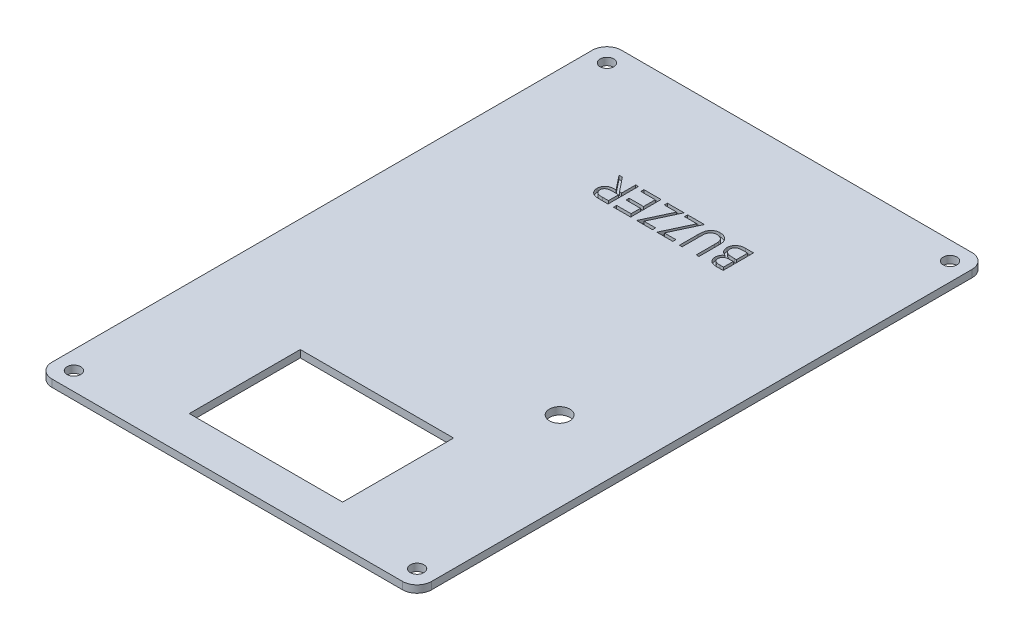
SolidWorks part; units mm, degrees
ref_plane "Front Plane" through (0, 0, 0) normal (0, 0, 1) x (1, 0, 0)
ref_plane "Top Plane" through (0, 0, 0) normal (0, 1, 0) x (1, 0, 0)
ref_plane "Right Plane" through (0, 0, 0) normal (1, 0, 0) x (0, 0, -1)
sketch "Sketch1" plane through (0, 0, 0) normal (0, 1, 0) x (1, 0, 0)
  line L1 (-34.4208, 88.2047) -> (31.6192, 88.2047)
  line L2 (-34.4208, 88.2047) -> (-34.4208, -10.8553)
  line L3 (-34.4208, -10.8553) -> (31.6192, -10.8553)
  line L4 (31.6192, 88.2047) -> (31.6192, -10.8553)
  line L6 (31.6192, -8.3153) -> (31.6192, -10.8553) construction
  line L7 (31.6192, -10.8553) -> (29.0792, -10.8553) construction
  line L8 (29.0792, -10.8553) -> (-31.8808, -10.8553) construction
  line L9 (-31.8808, -10.8553) -> (-34.4208, -10.8553) construction
  line L10 (-34.4208, -10.8553) -> (-34.4208, -8.3153) construction
  line L11 (-31.8808, 88.2047) -> (-34.4208, 88.2047) construction
  line L12 (-34.4208, 88.2047) -> (-34.4208, 85.6647) construction
  arc A3 (-31.8808, 88.2047) -> (-34.4208, 85.6647) centre (-31.8808, 85.6647) ccw construction
  point P4 (0, 0)
  point P12 (31.6192, 88.2047)
  point P21 (0, 0)
extrude "Boss-Extrude1" add sketch "Sketch1" along normal blind 1.27
fillet "Fillet1" radius 2.54 4 edges at (-34.4208, 0.635, -88.2047) (31.6192, 0.635, -88.2047) (31.6192, 0.635, 10.8553) (-34.4208, 0.635, 10.8553)
sketch "Sketch3" plane through (0, 1.27, 0) normal (0, 1, 0) x (1, 0, 0)
  line L0 (11.9342, 5.5277) -> (31.6192, 5.5277) construction
  line L1 (-14.7358, 5.5277) -> (-34.4208, 5.5277) construction
  line L5 (-34.4208, 85.6647) -> (-34.4208, -8.3153) construction
  line L6 (31.6192, -8.3153) -> (31.6192, 85.6647) construction
  line L7 (11.9342, -4.1243) -> (-14.7358, -4.1243)
  line L8 (11.9342, -4.1243) -> (11.9342, 15.1797)
  line L9 (11.9342, 15.1797) -> (-14.7358, 15.1797)
  line L10 (-14.7358, -4.1243) -> (-14.7358, 15.1797)
  line L11 (-34.4208, 85.6647) -> (-34.4208, -8.3153) construction
  line L12 (31.6192, -8.3153) -> (31.6192, 85.6647) construction
  line L19 (31.6192, 88.2047) -> (-34.4208, 88.2047)
  line L20 (31.6192, -10.8553) -> (31.6192, 88.2047)
  line L21 (-34.4208, -10.8553) -> (31.6192, -10.8553)
  line L22 (-34.4208, 88.2047) -> (-34.4208, -10.8553)
  line L23 (31.6192, 88.2047) -> (-34.4208, 88.2047) construction
  line L24 (31.6192, -10.8553) -> (31.6192, 88.2047) construction
  line L25 (-34.4208, -10.8553) -> (31.6192, -10.8553) construction
  line L26 (-34.4208, 88.2047) -> (-34.4208, -10.8553) construction
  dimension "D1" = 13.462
  dimension "D6" = 26.67
  dimension "D7" = 19.304
  dimension "D8" = 0
extrude "Cut-Extrude6" cut sketch "Sketch3" against normal through all and the other way through all
sketch "Sketch4" plane through (0, 1.27, 0) normal (0, 1, 0) x (1, 0, 0)
  line L0 (31.6192, 69.1547) -> (-34.4208, 69.1547) construction
  line L1 (31.6192, -8.3153) -> (31.6192, 85.6647) construction
  line L2 (-34.4208, 85.6647) -> (-34.4208, -8.3153) construction
  line L3 (29.0792, 88.2047) -> (-31.8808, 88.2047) construction
  text T0 "BUZZER" font "Century Gothic" height in points 20
  dimension "D1" = 19.05
extrude "Cut-Extrude7" cut sketch "Sketch4" against normal blind 0.635
sketch "Sketch5" plane through (0, 1.27, 0) normal (0, 1, 0) x (-1, 0, 0)
  line L0 (-17.6799, -27.8797) -> (-11.9342, -15.1797) construction
  line L1 (-17.6799, -27.8797) -> (-31.6192, -27.8797) construction
  line L2 (-31.6192, 8.3153) -> (-31.6192, -85.6647) construction
  circle A0 centre (-17.6799, -27.8797) radius 1.778
  dimension "D1" = 3.556
  dimension "D2" = 12.7
extrude "Cut-Extrude8" cut sketch "Sketch5" against normal through all
sketch "Sketch6" plane through (0, 1.27, 0) normal (0, 1, 0) x (1, 0, 0)
  circle A0 centre (28.4442, -7.6803) radius 1.1906
  circle A1 centre (28.4442, -7.6803) radius 1.1906 construction
  circle A2 centre (28.4442, -7.6803) radius 1.1906 construction
  circle A3 centre (-31.2458, -7.6803) radius 1.1906
  circle A4 centre (-31.2458, -7.6803) radius 1.1906 construction
  circle A5 centre (-31.2458, -7.6803) radius 1.1906 construction
  circle A6 centre (-31.2458, 85.0297) radius 1.1906 construction
  circle A7 centre (-31.2458, 85.0297) radius 1.1906 construction
  circle A8 centre (-31.2458, 85.0297) radius 1.1906
  circle A9 centre (28.4442, 85.0297) radius 1.1906 construction
  circle A10 centre (28.4442, 85.0297) radius 1.1906 construction
  circle A11 centre (28.4442, 85.0297) radius 1.1906
extrude "Cut-Extrude9" cut sketch "Sketch6" against normal through all
